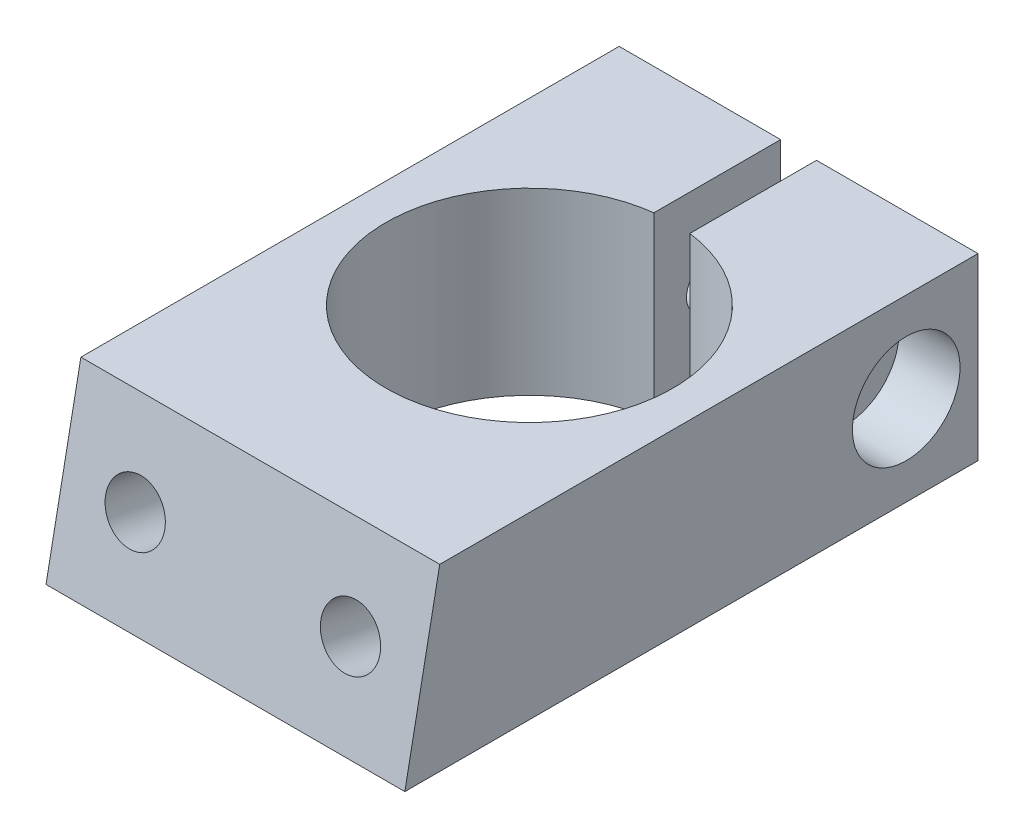
SolidWorks part; units mm, degrees
material "1060 合金"
ref_plane "前视基准面" through (0, 0, 0) normal (0, 0, 1) x (1, 0, 0)
ref_plane "上视基准面" through (0, 0, 0) normal (0, 1, 0) x (1, 0, 0)
ref_plane "右视基准面" through (0, 0, 0) normal (1, 0, 0) x (0, 0, -1)
sketch "草图1" plane through (0, 0, 0) normal (1, 0, 0) x (0, 0, -1)
  line L0 (0, 0) -> (1.9438, 10)
  line L1 (0, 0) -> (31.9438, 0)
  line L2 (1.9438, 10) -> (31.9438, 10)
  line L3 (31.9438, 0) -> (31.9438, 10)
  dimension "D1" = 79
  dimension "D2" = 30
  dimension "D3" = 10
extrude "凸台-拉伸1" add sketch "草图1" along normal mid plane 20
sketch "草图2" plane through (0, 10, 0) normal (0, 1, 0) x (1, 0, 0)
  line L0 (0, 0) -> (0, 34.2128) construction
  line L1 (10, 31.9438) -> (-10, 31.9438) construction
  line L3 (-1, 31.9438) -> (1, 31.9438)
  line L4 (-1, 31.9438) -> (-1, 24.8811)
  line L6 (1, 31.9438) -> (1, 24.8811)
  line L7 (-1, 31.9438) -> (1, 24.8811) construction
  line L8 (-1, 24.8811) -> (1, 31.9438) construction
  arc A0 (-1, 24.8811) -> (1, 24.8811) centre (0, 16.9438) ccw
  point P7 (0, 28.4124)
  dimension "D1" = 15
  dimension "D2" = 16
  dimension "D3" = 2
extrude "切除-拉伸1" cut sketch "草图2" against normal through all
hole_wizard "M4 螺纹孔1" positions "草图4" profile "草图3" tap size "M4" standard "GB"
sketch "草图4" plane through (0, 0, 0) normal (0, 0.1908, 0.9816) x (1, 0, 0)
  line L0 (0, 0) -> (0, 10.1146) construction
  line L1 (10, 0) -> (-10, 0) construction
  line L4 (10, 5.0936) -> (-12.5082, 5.0936) construction
  line L5 (10, 10.1872) -> (10, 0) construction
  point P0 (-6, 5.0936)
  point P19 (6, 5.0936)
  dimension "D1" = 12
cosmetic thread "孔螺蚊线1"
cosmetic thread "孔螺蚊线2"
sketch "草图3" plane through (-6, 5, -0.9719) normal (1, 0, 0) x (0, -0.9816, 0.1908)
  line L0 (0, 0) -> (0, 10.4914)
  line L1 (0, 10.4914) -> (1.65, 9.5)
  line L2 (1.65, 9.5) -> (1.65, 0)
  line L5 (1.65, 0) -> (0, 0)
  line L10 (0, 10.4914) -> (-1.65, 9.5) construction
  line L11 (0, -6.35) -> (0, 107.95) construction
  dimension "螺纹孔钻头直径" = 3.3
  dimension "螺纹孔钻头深度" = 9.5
  dimension "导头角度" = 118
hole_wizard "打孔尺寸(%根据)内六角圆柱头螺钉的类型2" positions "草图6" profile "草图5" counterbore size "M3" standard "GB"
sketch "草图6" plane through (10, 0, 0) normal (1, 0, 0) x (0, 0, -1)
  line L0 (31.9438, 0) -> (31.9438, 10) construction
  point P0 (27.9438, 5)
  dimension "D1" = 4
sketch "草图5" plane through (10, 5, -27.9438) normal (0, 1, 0) x (0, 0, -1)
  line L0 (0, 0) -> (0, 10.9614)
  line L1 (0, 10.9614) -> (1.6, 10)
  line L2 (1.6, 10) -> (1.6, 3.4)
  line L3 (1.6, 3.4) -> (3, 3.4)
  line L4 (3, 3.4) -> (3, 0)
  line L5 (3, 0) -> (0, 0)
  line L10 (0, 10.9614) -> (-1.6, 10) construction
  line L11 (0, -6.35) -> (0, 107.95) construction
  dimension "孔直径" = 3.2
  dimension "孔深度" = 10
  dimension "柱形沉头孔直径" = 6
  dimension "柱形沉头孔深度" = 3.4
  dimension "导头角度" = 118
hole_wizard "M3 螺纹孔1" positions "草图8" profile "草图7" tap size "M3" standard "GB" end condition up to next
sketch "草图8" plane through (-10, 0, 0) normal (-1, 0, 0) x (0, 0, 1)
  point P0 (-27.9438, 5)
cosmetic thread "孔螺蚊线3"
sketch "草图7" plane through (-10, 5, -27.9438) normal (0, 1, 0) x (0, 0, 1)
  line L0 (0, 0) -> (0, 9)
  line L1 (0, 9) -> (1.25, 9)
  line L2 (1.25, 9) -> (1.25, 0)
  line L5 (1.25, 0) -> (0, 0)
  line L11 (0, -6.35) -> (0, 107.95) construction
  dimension "通孔螺纹孔钻头直径" = 2.5
  dimension "通孔螺纹孔钻头深度" = 9
